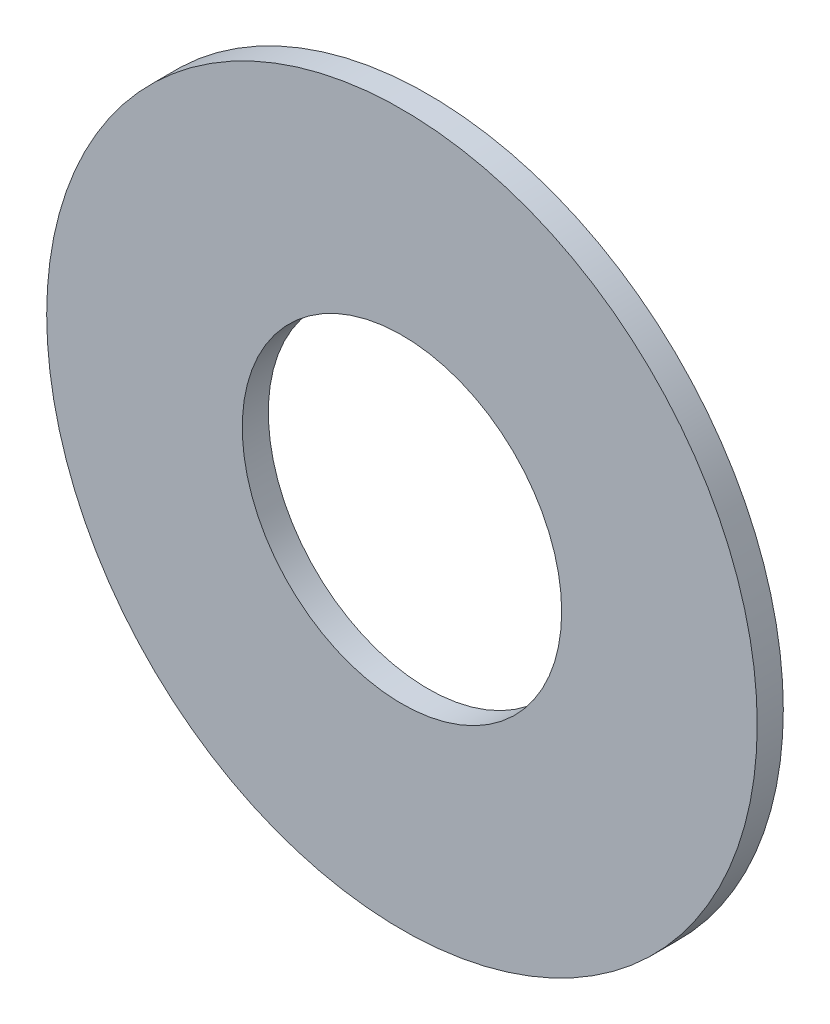
SolidWorks part; units mm, degrees
ref_plane "Спереди" through (0, 0, 0) normal (0, 0, 1) x (1, 0, 0)
ref_plane "Сверху" through (0, 0, 0) normal (0, 1, 0) x (1, 0, 0)
ref_plane "Справа" through (0, 0, 0) normal (1, 0, 0) x (0, 0, -1)
sketch "Эскиз1" plane through (0, 0, 0) normal (0, 0, 1) x (1, 0, 0)
  circle A0 centre (0, 0) radius 10.9
  circle A1 centre (0, 0) radius 4.9
  dimension "D1" = 21.8
  dimension "D2" = 9.8
extrude "Бобышка-Вытянуть1" add sketch "Эскиз1" along normal blind 0.8
